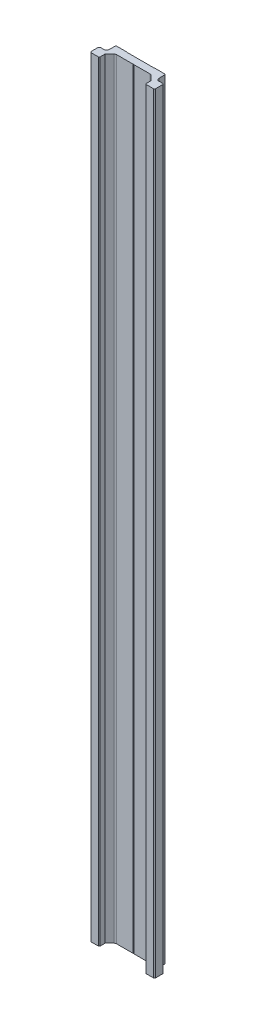
SolidWorks part; units mm, degrees
ref_plane "Front Plane" through (0, 0, 0) normal (0, 0, 1) x (1, 0, 0)
ref_plane "Top Plane" through (0, 0, 0) normal (0, 1, 0) x (1, 0, 0)
ref_plane "Right Plane" through (0, 0, 0) normal (1, 0, 0) x (0, 0, -1)
ref_plane "Plane1" through (0, 200, 0) normal (0, 1, 0) x (1, 0, 0)
sketch "Sketch1" plane through (0, 200, 0) normal (0, 1, 0) x (1, 0, 0)
  line L0 (0, -3.8557) -> (0.25, -4)
  line L1 (0.25, -4) -> (9.0787, -4)
  line L2 (10.1394, -4.4394) -> (12.5, -6.8)
  line L3 (12.5, -6.8) -> (12.5, -9.5)
  line L4 (12.5, -9.5) -> (13, -10)
  line L5 (13, -10) -> (17, -10)
  line L6 (17, -10) -> (17.5, -9.5)
  line L7 (17.5, -9.5) -> (17.5, -5.5)
  line L8 (17.5, -5.5) -> (17, -5)
  line L9 (17, -5) -> (14.3, -5)
  line L10 (14.3, -5) -> (14.0858, -4.7858)
  line L11 (13.5, -3.3716) -> (13.5, -0.3)
  line L12 (13.5, -0.3) -> (13.2, 0)
  line L13 (13.2, 0) -> (7.5, 0)
  line L14 (7.5, 0) -> (7.4, -0.1)
  line L15 (7.4, -0.1) -> (-7.4, -0.1)
  line L16 (-7.4, -0.1) -> (-7.5, 0)
  line L17 (-7.5, 0) -> (-13.2, 0)
  line L18 (-13.2, 0) -> (-13.5, -0.3)
  line L19 (-13.5, -0.3) -> (-13.5, -3.3716)
  line L20 (-14.0858, -4.7858) -> (-14.3, -5)
  line L21 (-14.3, -5) -> (-17, -5)
  line L22 (-17, -5) -> (-17.5, -5.5)
  line L23 (-17.5, -5.5) -> (-17.5, -9.5)
  line L24 (-17.5, -9.5) -> (-17, -10)
  line L25 (-17, -10) -> (-13, -10)
  line L26 (-13, -10) -> (-12.5, -9.5)
  line L27 (-12.5, -9.5) -> (-12.5, -6.8)
  line L28 (-12.5, -6.8) -> (-10.1394, -4.4394)
  line L29 (-9.0787, -4) -> (-0.25, -4)
  line L30 (-0.25, -4) -> (0, -3.8557)
  arc A0 (9.0787, -4) -> (10.1394, -4.4394) centre (9.0787, -5.5) cw
  arc A1 (14.0858, -4.7858) -> (13.5, -3.3716) centre (15.5, -3.3716) cw
  arc A2 (-13.5, -3.3716) -> (-14.0858, -4.7858) centre (-15.5, -3.3716) cw
  arc A3 (-10.1394, -4.4394) -> (-9.0787, -4) centre (-9.0787, -5.5) cw
extrude "Boss-Extrude1" add sketch "Sketch1" against normal blind 418
